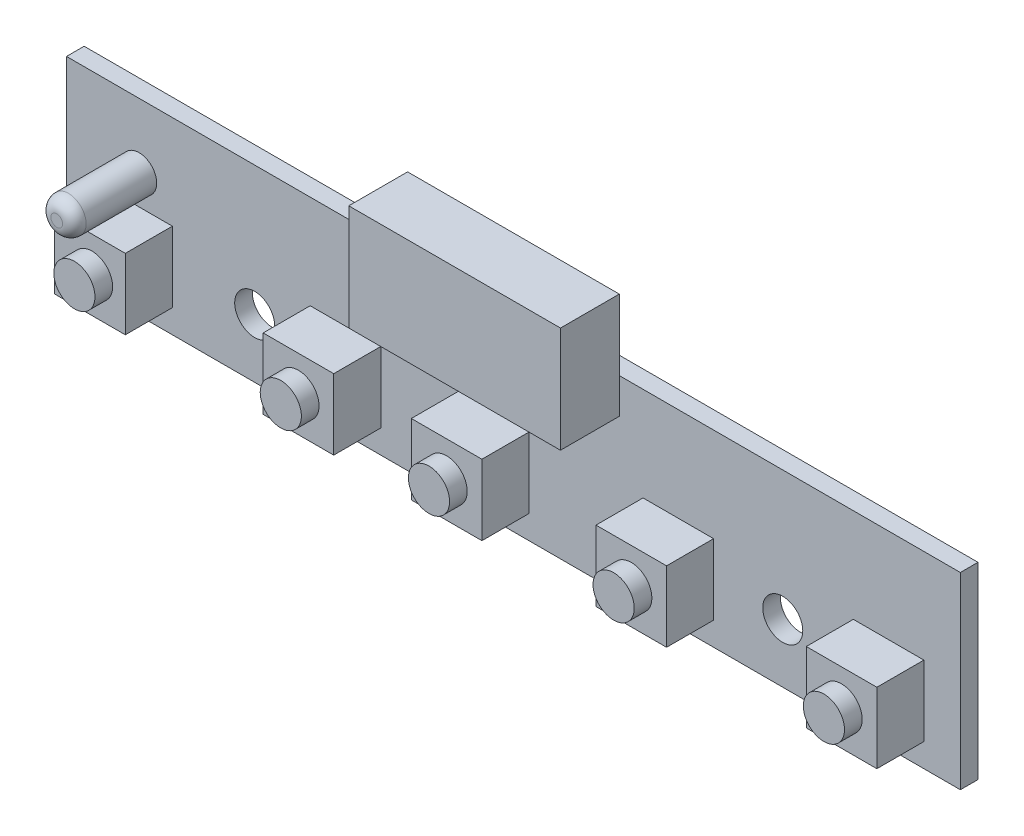
SolidWorks part; units mm, degrees
ref_plane "Front Plane" through (0, 0, 0) normal (0, 0, 1) x (1, 0, 0)
ref_plane "Top Plane" through (0, 0, 0) normal (0, 1, 0) x (1, 0, 0)
ref_plane "Right Plane" through (0, 0, 0) normal (1, 0, 0) x (0, 0, -1)
sketch "Sketch1" plane through (0, 0, 0) normal (0, 0, 1) x (1, 0, 0)
  line L1 (0, 0) -> (76, 0)
  line L2 (0, 0) -> (0, 16)
  line L3 (0, 16) -> (76, 16)
  line L4 (76, 0) -> (76, 16)
  dimension "D1" = 76
  dimension "D2" = 16
extrude "Boss-Extrude1" add sketch "Sketch1" along normal blind 1.5
sketch "Sketch2" plane through (0, 0, 1.5) normal (0, 0, 1) x (1, 0, 0)
  line L1 (3, 2) -> (9, 2)
  line L2 (3, 2) -> (3, 8)
  line L3 (3, 8) -> (9, 8)
  line L4 (9, 2) -> (9, 8)
  line L5 (0, 16) -> (0, 0) construction
  line L6 (0, 0) -> (76, 0) construction
  dimension "D1" = 6
  dimension "D2" = 6
  dimension "D3" = 3
  dimension "D4" = 2
extrude "Boss-Extrude2" add sketch "Sketch2" along normal blind 4
sketch "Sketch3" plane through (0, 0, 5.5) normal (0, 0, 1) x (1, 0, 0)
  line L0 (0, 16) -> (0, 0) construction
  line L1 (3, 2) -> (9, 2) construction
  circle A0 centre (6.17, 5) radius 1.75
  dimension "D1" = 3.5
  dimension "D2" = 6.17
  dimension "D3" = 3
extrude "Boss-Extrude3" add sketch "Sketch3" along normal blind 1.5
sketch "Sketch7" plane through (16.2424, -0.5205, 1.5) normal (0, 0, 1) x (1, 0, 0)
  line L0 (-16.2424, 16.5205) -> (-16.2424, 0.5205) construction
  line L1 (4.4776, 2.5205) -> (10.4776, 2.5205)
  line L2 (4.4776, 2.5205) -> (4.4776, 8.5205)
  line L3 (4.4776, 8.5205) -> (10.4776, 8.5205)
  line L4 (10.4776, 2.5205) -> (10.4776, 8.5205)
  line L7 (-16.2424, 0.5205) -> (59.7576, 0.5205) construction
  dimension "D1" = 6
  dimension "D2" = 6
  dimension "D3" = 20.72
  dimension "D4" = 2
extrude "Boss-Extrude4" add sketch "Sketch7" along normal blind 4
sketch "Sketch9" plane through (16.2424, -0.5205, 5.5) normal (0, 0, 1) x (1, 0, 0)
  line L1 (4.4776, 2.5205) -> (10.4776, 2.5205) construction
  circle A0 centre (7.4776, 5.5205) radius 1.75
  dimension "D1" = 3.5
  dimension "D3" = 3
extrude "Boss-Extrude5" add sketch "Sketch9" along normal blind 1.5
sketch "Sketch11" plane through (28.5953, 2.581, 1.5) normal (0, 0, 1) x (1, 0, 0)
  line L0 (-28.5953, 13.419) -> (-28.5953, -2.581) construction
  line L1 (4.7247, -0.581) -> (10.7247, -0.581)
  line L2 (4.7247, -0.581) -> (4.7247, 5.419)
  line L3 (4.7247, 5.419) -> (10.7247, 5.419)
  line L4 (10.7247, -0.581) -> (10.7247, 5.419)
  line L7 (-28.5953, -2.581) -> (47.4047, -2.581) construction
  dimension "D1" = 6
  dimension "D2" = 6
  dimension "D3" = 33.32
  dimension "D4" = 2
extrude "Boss-Extrude6" add sketch "Sketch11" along normal blind 4
sketch "Sketch13" plane through (28.5953, 2.581, 5.5) normal (0, 0, 1) x (1, 0, 0)
  line L1 (4.7247, -0.581) -> (10.7247, -0.581) construction
  line L2 (4.7247, 5.419) -> (4.7247, -0.581) construction
  circle A0 centre (7.7247, 2.419) radius 1.75
  dimension "D1" = 3.5
  dimension "D2" = 3
  dimension "D3" = 3
  dimension "D4" = 3
extrude "Boss-Extrude7" add sketch "Sketch13" along normal blind 1.5
sketch "Sketch15" plane through (42.2061, 2.0896, 1.5) normal (0, 0, 1) x (1, 0, 0)
  line L0 (-42.2061, 13.9104) -> (-42.2061, -2.0896) construction
  line L1 (6.8139, -0.0896) -> (12.8139, -0.0896)
  line L2 (6.8139, -0.0896) -> (6.8139, 5.9104)
  line L3 (6.8139, 5.9104) -> (12.8139, 5.9104)
  line L4 (12.8139, -0.0896) -> (12.8139, 5.9104)
  line L7 (-42.2061, -2.0896) -> (33.7939, -2.0896) construction
  dimension "D1" = 6
  dimension "D2" = 6
  dimension "D3" = 49.02
  dimension "D4" = 2
extrude "Boss-Extrude8" add sketch "Sketch15" along normal blind 4
sketch "Sketch17" plane through (42.2061, 2.0896, 5.5) normal (0, 0, 1) x (1, 0, 0)
  line L1 (6.8139, -0.0896) -> (12.8139, -0.0896) construction
  line L2 (6.8139, 5.9104) -> (6.8139, -0.0896) construction
  line L3 (6.8139, -0.0896) -> (12.8139, -0.0896) construction
  circle A0 centre (9.8139, 2.9104) radius 1.75
  dimension "D1" = 3.5
  dimension "D2" = 3
  dimension "D3" = 3
  dimension "D4" = 3
extrude "Boss-Extrude9" add sketch "Sketch17" along normal blind 1.5
sketch "Sketch19" plane through (52.6042, 1.0865, 1.5) normal (0, 0, 1) x (1, 0, 0)
  line L0 (-52.6042, 14.9135) -> (-52.6042, -1.0865) construction
  line L1 (14.2958, 0.9135) -> (20.2958, 0.9135)
  line L2 (14.2958, 0.9135) -> (14.2958, 6.9135)
  line L3 (14.2958, 6.9135) -> (20.2958, 6.9135)
  line L4 (20.2958, 0.9135) -> (20.2958, 6.9135)
  line L7 (-52.6042, -1.0865) -> (23.3958, -1.0865) construction
  dimension "D1" = 6
  dimension "D2" = 6
  dimension "D3" = 66.9
  dimension "D4" = 2
extrude "Boss-Extrude10" add sketch "Sketch19" along normal blind 4
sketch "Sketch21" plane through (52.6042, 1.0865, 5.5) normal (0, 0, 1) x (1, 0, 0)
  line L3 (14.2958, 6.9135) -> (14.2958, 0.9135) construction
  line L4 (14.2958, 0.9135) -> (20.2958, 0.9135) construction
  circle A0 centre (17.2958, 3.9135) radius 1.75
  dimension "D1" = 3.5
  dimension "D2" = 3
  dimension "D3" = 3
extrude "Boss-Extrude11" add sketch "Sketch21" along normal blind 1.5
sketch "Sketch23" plane through (0, 0, 1.5) normal (0, 0, 1) x (1, 0, 0)
  line L0 (0, 16) -> (0, 0) construction
  line L1 (76, 16) -> (0, 16) construction
  circle A0 centre (6.17, 10.5) radius 1.5
  dimension "D1" = 3
  dimension "D2" = 6.17
  dimension "D3" = 5.5
extrude "Boss-Extrude12" add sketch "Sketch23" along normal blind 7
fillet "Fillet1" radius 1 1 edges at (7.67, 10.5, 8.5)
sketch "Sketch24" plane through (0, 0, 1.5) normal (0, 0, 1) x (1, 0, 0)
  line L0 (0, 16) -> (0, 0) construction
  line L1 (29, 13) -> (47, 13)
  line L2 (29, 13) -> (29, 22)
  line L3 (29, 22) -> (47, 22)
  line L4 (47, 13) -> (47, 22)
  line L5 (76, 16) -> (0, 16) construction
  dimension "D1" = 18
  dimension "D2" = 9
  dimension "D3" = 29
  dimension "D4" = 3
extrude "Boss-Extrude13" add sketch "Sketch24" along normal blind 5
hole_wizard "M3 Clearance Hole2" positions "Sketch26" profile "Sketch27" hole size "M3" standard "ANSI Metric" end condition through all
sketch "Sketch26" plane through (0, 0, 1.5) normal (0, 0, 1) x (1, 0, 0)
  point P0 (16, 5)
  point P3 (60.9, 5)
sketch "Sketch27" plane through (16, 5, 1.5) normal (1, 0, 0) x (0, -1, 0)
  line L0 (0, 0) -> (0, 1.5)
  line L1 (0, 1.5) -> (1.7, 1.5)
  line L2 (1.7, 1.5) -> (1.7, 0)
  line L5 (1.7, 0) -> (0, 0)
  line L11 (0, -6.35) -> (0, 107.95) construction
  dimension "Thru Hole Dia." = 3.4
  dimension "Thru Hole Depth" = 1.5
